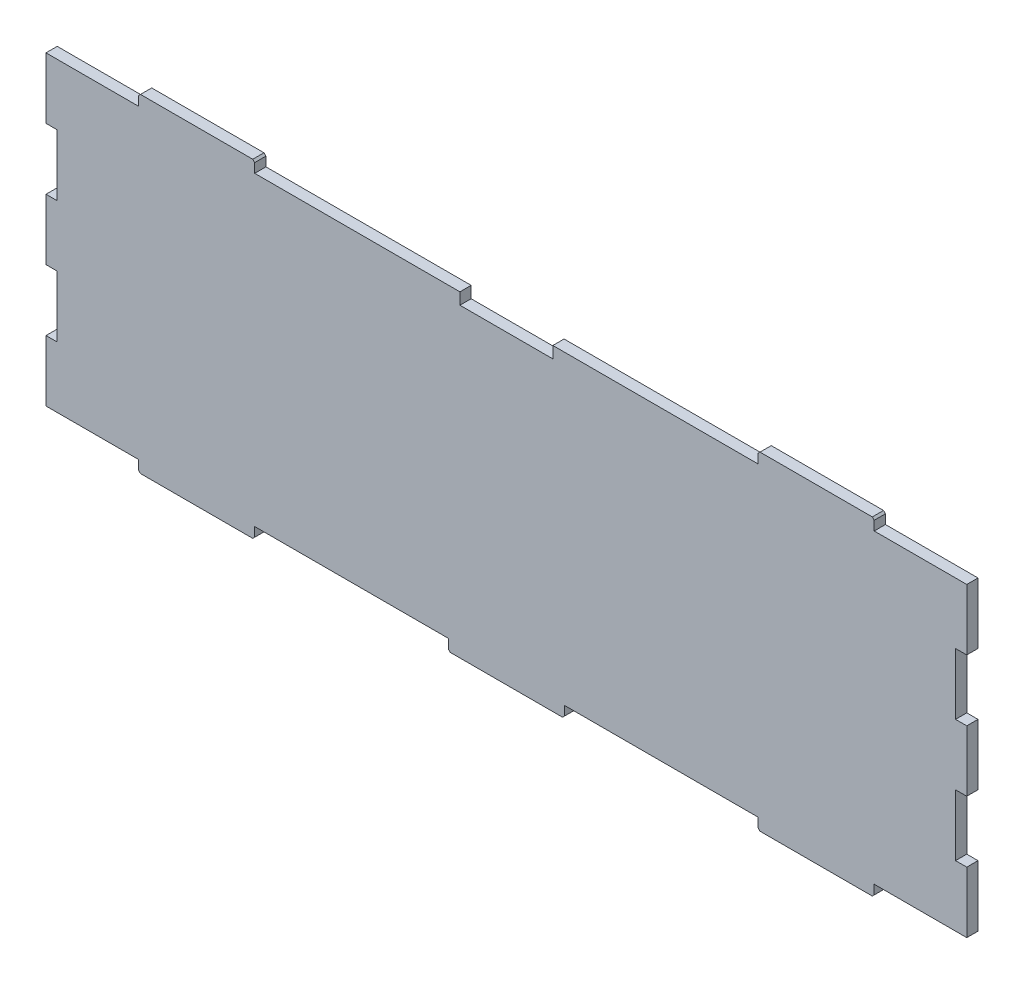
SolidWorks part; units mm, degrees
material "Acrylic (Medium-high impact)"
ref_plane "Front Plane" through (0, 0, 0) normal (0, 0, 1) x (1, 0, 0)
ref_plane "Top Plane" through (0, 0, 0) normal (0, 1, 0) x (1, 0, 0)
ref_plane "Right Plane" through (0, 0, 0) normal (1, 0, 0) x (0, 0, -1)
ref_plane "Plane1" through (0, 0, 135) normal (0, 0, 1) x (1, 0, 0)
sketch "Sketch1" plane through (0, 0, 135) normal (0, 0, 1) x (1, 0, 0)
  line L0 (-118.9, 2.9) -> (-95, 2.9)
  line L1 (-95, 2.9) -> (-95, 0.5)
  line L2 (-95, 0.5) -> (-94.5, 0)
  line L3 (-94.5, 0) -> (-65.5, 0)
  line L4 (-65.5, 0) -> (-65, 0.5)
  line L5 (-65, 0.5) -> (-65, 2.9)
  line L6 (-65, 2.9) -> (-15, 2.9)
  line L7 (-15, 2.9) -> (-15, 0.5)
  line L8 (-15, 0.5) -> (-14.5, 0)
  line L9 (-14.5, 0) -> (14.5, 0)
  line L10 (14.5, 0) -> (15, 0.5)
  line L11 (15, 0.5) -> (15, 2.9)
  line L12 (15, 2.9) -> (65, 2.9)
  line L13 (65, 2.9) -> (65, 0.5)
  line L14 (65, 0.5) -> (65.5, 0)
  line L15 (65.5, 0) -> (94.5, 0)
  line L16 (94.5, 0) -> (95, 0.5)
  line L17 (95, 0.5) -> (95, 2.9)
  line L18 (95, 2.9) -> (118.9, 2.9)
  line L19 (118.9, 2.9) -> (118.9, 18.675)
  line L20 (118.9, 18.675) -> (116, 18.675)
  line L21 (116, 18.675) -> (116, 34.525)
  line L22 (116, 34.525) -> (118.9, 34.525)
  line L23 (118.9, 34.525) -> (118.9, 50.275)
  line L24 (118.9, 50.275) -> (116, 50.275)
  line L25 (116, 50.275) -> (116, 66.125)
  line L26 (116, 66.125) -> (118.9, 66.125)
  line L27 (118.9, 66.125) -> (118.9, 81.9)
  line L28 (118.9, 81.9) -> (95, 81.9)
  line L29 (95, 81.9) -> (95, 84.3)
  line L30 (95, 84.3) -> (94.5, 84.8)
  line L31 (94.5, 84.8) -> (65.5, 84.8)
  line L32 (65.5, 84.8) -> (65, 84.3)
  line L33 (65, 84.3) -> (65, 81.9)
  line L34 (65, 81.9) -> (12, 81.9)
  line L35 (12, 81.9) -> (12, 78.9)
  line L36 (12, 78.9) -> (-12, 78.9)
  line L37 (-12, 78.9) -> (-12, 81.9)
  line L38 (-12, 81.9) -> (-65, 81.9)
  line L39 (-65, 81.9) -> (-65, 84.3)
  line L40 (-65, 84.3) -> (-65.5, 84.8)
  line L41 (-65.5, 84.8) -> (-94.5, 84.8)
  line L42 (-94.5, 84.8) -> (-95, 84.3)
  line L43 (-95, 84.3) -> (-95, 81.9)
  line L44 (-95, 81.9) -> (-118.9, 81.9)
  line L45 (-118.9, 81.9) -> (-118.9, 66.125)
  line L46 (-118.9, 66.125) -> (-116, 66.125)
  line L47 (-116, 66.125) -> (-116, 50.275)
  line L48 (-116, 50.275) -> (-118.9, 50.275)
  line L49 (-118.9, 50.275) -> (-118.9, 34.525)
  line L50 (-118.9, 34.525) -> (-116, 34.525)
  line L51 (-116, 34.525) -> (-116, 18.675)
  line L52 (-116, 18.675) -> (-118.9, 18.675)
  line L53 (-118.9, 18.675) -> (-118.9, 2.9)
extrude "Boss-Extrude1" add sketch "Sketch1" along normal blind 2.9
